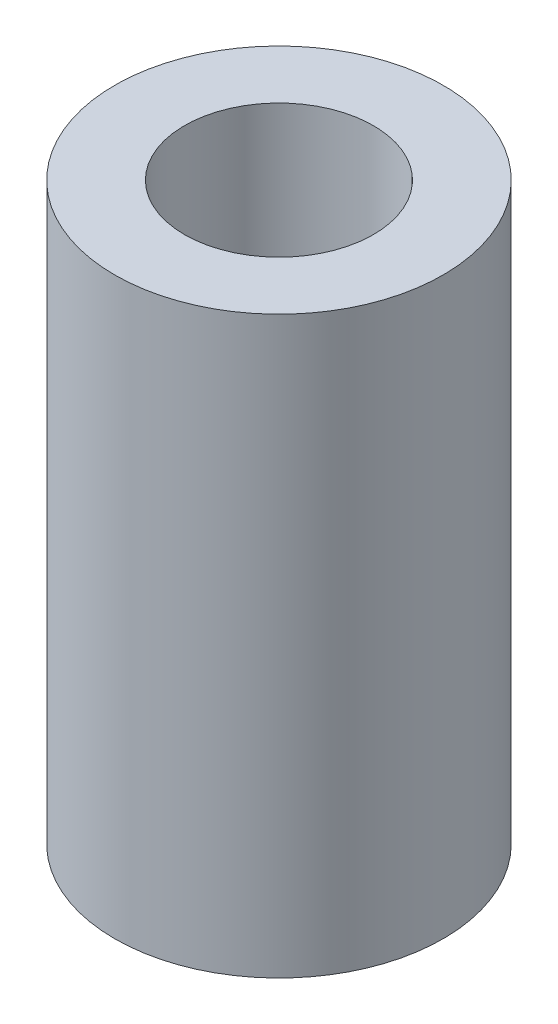
SolidWorks part; units mm, degrees
ref_plane "Front Plane" through (0, 0, 0) normal (0, 0, 1) x (1, 0, 0)
ref_plane "Top Plane" through (0, 0, 0) normal (0, 1, 0) x (1, 0, 0)
ref_plane "Right Plane" through (0, 0, 0) normal (1, 0, 0) x (0, 0, -1)
sketch "Sketch1" plane through (0, 0, 0) normal (0, 1, 0) x (1, 0, 0)
  circle A0 centre (0, 0) radius 2
  circle A1 centre (0, 0) radius 1.15
  dimension "D1" = 4
  dimension "D2" = 2.3
extrude "Boss-Extrude1" add sketch "Sketch1" along normal blind 7
